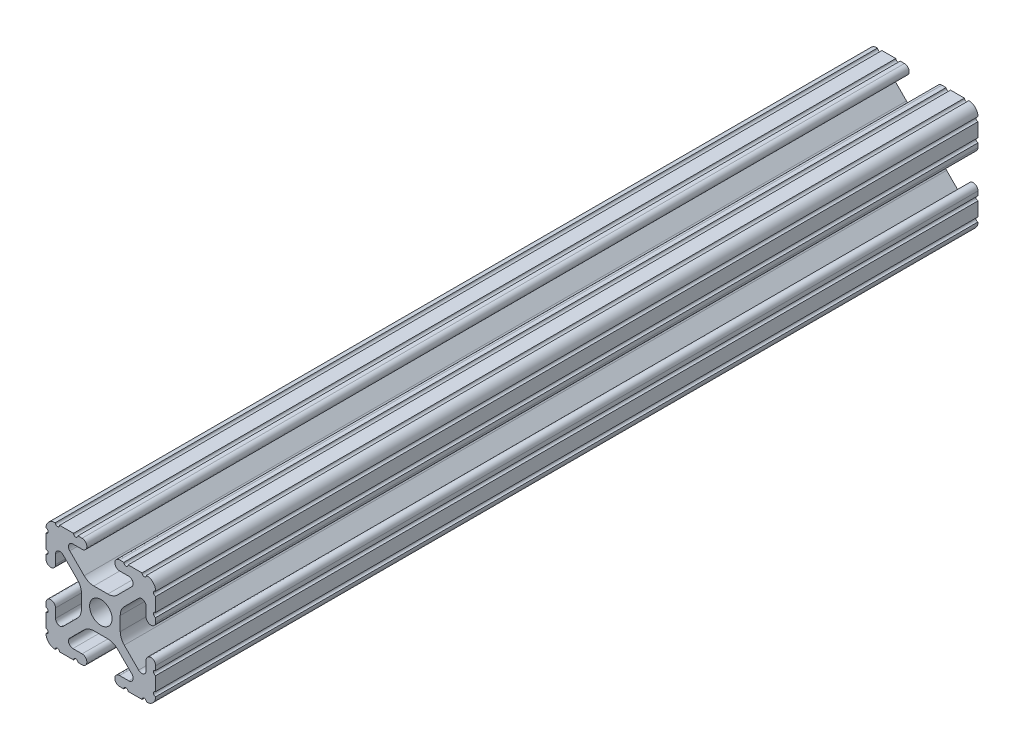
SolidWorks part; units mm, degrees
ref_plane "Front Plane" through (0, 0, 0) normal (0, 0, 1) x (1, 0, 0)
ref_plane "Top Plane" through (0, 0, 0) normal (0, 1, 0) x (1, 0, 0)
ref_plane "Right Plane" through (0, 0, 0) normal (1, 0, 0) x (0, 0, -1)
ref_plane "Plane1" through (0, 0, -25.4) normal (0, 0, -1) x (-1, 0, 0)
sketch "Sketch1" plane through (0, 0, -25.4) normal (0, 0, -1) x (-1, 0, 0)
  line L0 (12.7, -9.5504) -> (12.7, -6.3331)
  line L1 (12.7, -5.3171) -> (12.7, -4.3434)
  line L2 (10.4902, -4.3434) -> (10.4902, -6.4748)
  line L3 (8.7558, -7.1932) -> (5.4257, -3.8632)
  line L4 (4.4958, -1.6181) -> (4.4958, 1.6181)
  line L5 (5.4257, 3.8632) -> (8.7558, 7.1932)
  line L6 (10.4902, 6.4748) -> (10.4902, 4.3434)
  line L7 (12.7, 4.3434) -> (12.7, 5.3171)
  line L8 (12.7, 6.3331) -> (12.7, 9.5504)
  line L9 (9.5504, 12.7) -> (6.3331, 12.7)
  line L10 (5.3171, 12.7) -> (4.3434, 12.7)
  line L11 (4.3434, 10.4902) -> (6.4748, 10.4902)
  line L12 (7.1932, 8.7558) -> (3.8632, 5.4257)
  line L13 (1.6181, 4.4958) -> (-1.6181, 4.4958)
  line L14 (-3.8632, 5.4257) -> (-7.1932, 8.7558)
  line L15 (-6.4748, 10.4902) -> (-4.3434, 10.4902)
  line L16 (-4.3434, 12.7) -> (-5.3171, 12.7)
  line L17 (-6.3331, 12.7) -> (-9.5504, 12.7)
  line L18 (-12.7, 9.5504) -> (-12.7, 6.3331)
  line L19 (-12.7, 5.3171) -> (-12.7, 4.3434)
  line L20 (-10.4902, 4.3434) -> (-10.4902, 6.4748)
  line L21 (-8.7558, 7.1932) -> (-5.4257, 3.8632)
  line L22 (-4.4958, 1.6181) -> (-4.4958, -1.6181)
  line L23 (-5.4257, -3.8632) -> (-8.7558, -7.1932)
  line L24 (-10.4902, -6.4748) -> (-10.4902, -4.3434)
  line L25 (-12.7, -4.3434) -> (-12.7, -5.3171)
  line L26 (-12.7, -6.3331) -> (-12.7, -9.5504)
  line L27 (-9.5504, -12.7) -> (-6.3331, -12.7)
  line L28 (-5.3171, -12.7) -> (-4.3434, -12.7)
  line L29 (-4.3434, -10.4902) -> (-6.4748, -10.4902)
  line L30 (-7.1932, -8.7558) -> (-3.8632, -5.4257)
  line L31 (-1.6181, -4.4958) -> (1.6181, -4.4958)
  line L32 (3.8632, -5.4257) -> (7.1932, -8.7558)
  line L33 (6.4748, -10.4902) -> (4.3434, -10.4902)
  line L34 (4.3434, -12.7) -> (5.3171, -12.7)
  line L35 (6.3331, -12.7) -> (9.5504, -12.7)
  arc A0 (12.6998, -10.5664) -> (12.7, -9.5504) centre (12.7, -10.0584) cw
  arc A1 (12.7, -6.3331) -> (12.7, -5.3171) centre (12.7, -5.8251) cw
  arc A2 (12.7, -4.3434) -> (10.4902, -4.3434) centre (11.5951, -4.3434) ccw
  arc A3 (10.4902, -6.4748) -> (8.7558, -7.1932) centre (9.4742, -6.4748) cw
  arc A4 (5.4257, -3.8632) -> (4.4958, -1.6181) centre (7.6708, -1.6181) cw
  arc A5 (4.4958, 1.6181) -> (5.4257, 3.8632) centre (7.6708, 1.6181) cw
  arc A6 (8.7558, 7.1932) -> (10.4902, 6.4748) centre (9.4742, 6.4748) cw
  arc A7 (10.4902, 4.3434) -> (12.7, 4.3434) centre (11.5951, 4.3434) ccw
  arc A8 (12.7, 5.3171) -> (12.7, 6.3331) centre (12.7, 5.8251) cw
  arc A9 (12.7, 9.5504) -> (12.6998, 10.5664) centre (12.7, 10.0584) cw
  arc A10 (12.6998, 10.5664) -> (10.5664, 12.6998) centre (10.5918, 10.5918) ccw
  arc A11 (10.5664, 12.6998) -> (9.5504, 12.7) centre (10.0584, 12.7) cw
  arc A12 (6.3331, 12.7) -> (5.3171, 12.7) centre (5.8251, 12.7) cw
  arc A13 (4.3434, 12.7) -> (4.3434, 10.4902) centre (4.3434, 11.5951) ccw
  arc A14 (6.4748, 10.4902) -> (7.1932, 8.7558) centre (6.4748, 9.4742) cw
  arc A15 (3.8632, 5.4257) -> (1.6181, 4.4958) centre (1.6181, 7.6708) cw
  arc A16 (-1.6181, 4.4958) -> (-3.8632, 5.4257) centre (-1.6181, 7.6708) cw
  arc A17 (-7.1932, 8.7558) -> (-6.4748, 10.4902) centre (-6.4748, 9.4742) cw
  arc A18 (-4.3434, 10.4902) -> (-4.3434, 12.7) centre (-4.3434, 11.5951) ccw
  arc A19 (-5.3171, 12.7) -> (-6.3331, 12.7) centre (-5.8251, 12.7) cw
  arc A20 (-9.5504, 12.7) -> (-10.5664, 12.6998) centre (-10.0584, 12.7) cw
  arc A21 (-10.5664, 12.6998) -> (-12.6998, 10.5664) centre (-10.5918, 10.5918) ccw
  arc A22 (-12.6998, 10.5664) -> (-12.7, 9.5504) centre (-12.7, 10.0584) cw
  arc A23 (-12.7, 6.3331) -> (-12.7, 5.3171) centre (-12.7, 5.8251) cw
  arc A24 (-12.7, 4.3434) -> (-10.4902, 4.3434) centre (-11.5951, 4.3434) ccw
  arc A25 (-10.4902, 6.4748) -> (-8.7558, 7.1932) centre (-9.4742, 6.4748) cw
  arc A26 (-5.4257, 3.8632) -> (-4.4958, 1.6181) centre (-7.6708, 1.6181) cw
  arc A27 (-4.4958, -1.6181) -> (-5.4257, -3.8632) centre (-7.6708, -1.6181) cw
  arc A28 (-8.7558, -7.1932) -> (-10.4902, -6.4748) centre (-9.4742, -6.4748) cw
  arc A29 (-10.4902, -4.3434) -> (-12.7, -4.3434) centre (-11.5951, -4.3434) ccw
  arc A30 (-12.7, -5.3171) -> (-12.7, -6.3331) centre (-12.7, -5.8251) cw
  arc A31 (-12.7, -9.5504) -> (-12.6998, -10.5664) centre (-12.7, -10.0584) cw
  arc A32 (-12.6998, -10.5664) -> (-10.5664, -12.6998) centre (-10.5918, -10.5918) ccw
  arc A33 (-10.5664, -12.6998) -> (-9.5504, -12.7) centre (-10.0584, -12.7) cw
  arc A34 (-6.3331, -12.7) -> (-5.3171, -12.7) centre (-5.8251, -12.7) cw
  arc A35 (-4.3434, -12.7) -> (-4.3434, -10.4902) centre (-4.3434, -11.5951) ccw
  arc A36 (-6.4748, -10.4902) -> (-7.1932, -8.7558) centre (-6.4748, -9.4742) cw
  arc A37 (-3.8632, -5.4257) -> (-1.6181, -4.4958) centre (-1.6181, -7.6708) cw
  arc A38 (1.6181, -4.4958) -> (3.8632, -5.4257) centre (1.6181, -7.6708) cw
  arc A39 (7.1932, -8.7558) -> (6.4748, -10.4902) centre (6.4748, -9.4742) cw
  arc A40 (4.3434, -10.4902) -> (4.3434, -12.7) centre (4.3434, -11.5951) ccw
  arc A41 (5.3171, -12.7) -> (6.3331, -12.7) centre (5.8251, -12.7) cw
  arc A42 (9.5504, -12.7) -> (10.5664, -12.6998) centre (10.0584, -12.7) cw
  arc A43 (10.5664, -12.6998) -> (12.6998, -10.5664) centre (10.5918, -10.5918) ccw
  circle A44 centre (0, 0) radius 2.6035
extrude "Boss-Extrude1" add sketch "Sketch1" against normal blind 190.5
